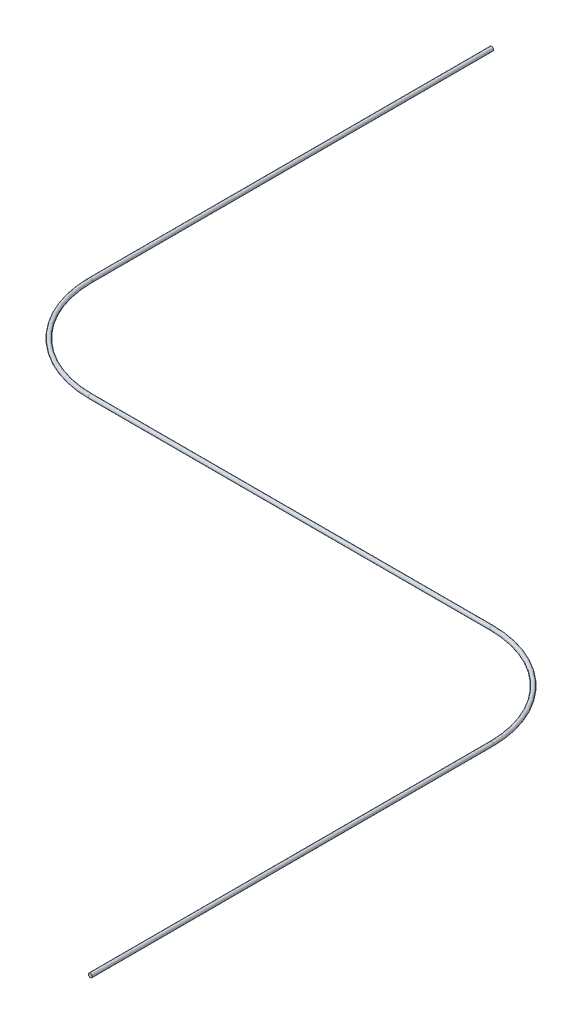
SolidWorks part; units mm, degrees
ref_plane "Front Plane" through (0, 0, 0) normal (0, 0, 1) x (1, 0, 0)
ref_plane "Top Plane" through (0, 0, 0) normal (0, 1, 0) x (1, 0, 0)
ref_plane "Right Plane" through (0, 0, 0) normal (1, 0, 0) x (0, 0, -1)
sketch "Sketch1" plane through (0, 0, 0) normal (0, 1, 0) x (1, 0, 0)
  line L0 (0, 0) -> (0, 400)
  line L1 (-100, 500) -> (-500, 500)
  line L2 (-600, 600) -> (-600, 1000)
  arc A0 (-600, 600) -> (-500, 500) centre (-500, 600) ccw
  arc A1 (0, 400) -> (-100, 500) centre (-100, 400) ccw
  point P9 (0, 500)
  dimension "D2" = 100
  dimension "D1" = 500
sketch "Sketch2" plane through (0, 0, 0) normal (0, 0, 1) x (1, 0, 0)
  circle A0 centre (0, 0) radius 2
  dimension "D1" = 4
sweep "Sweep1" add profiles "Sketch2" path "Sketch1"
